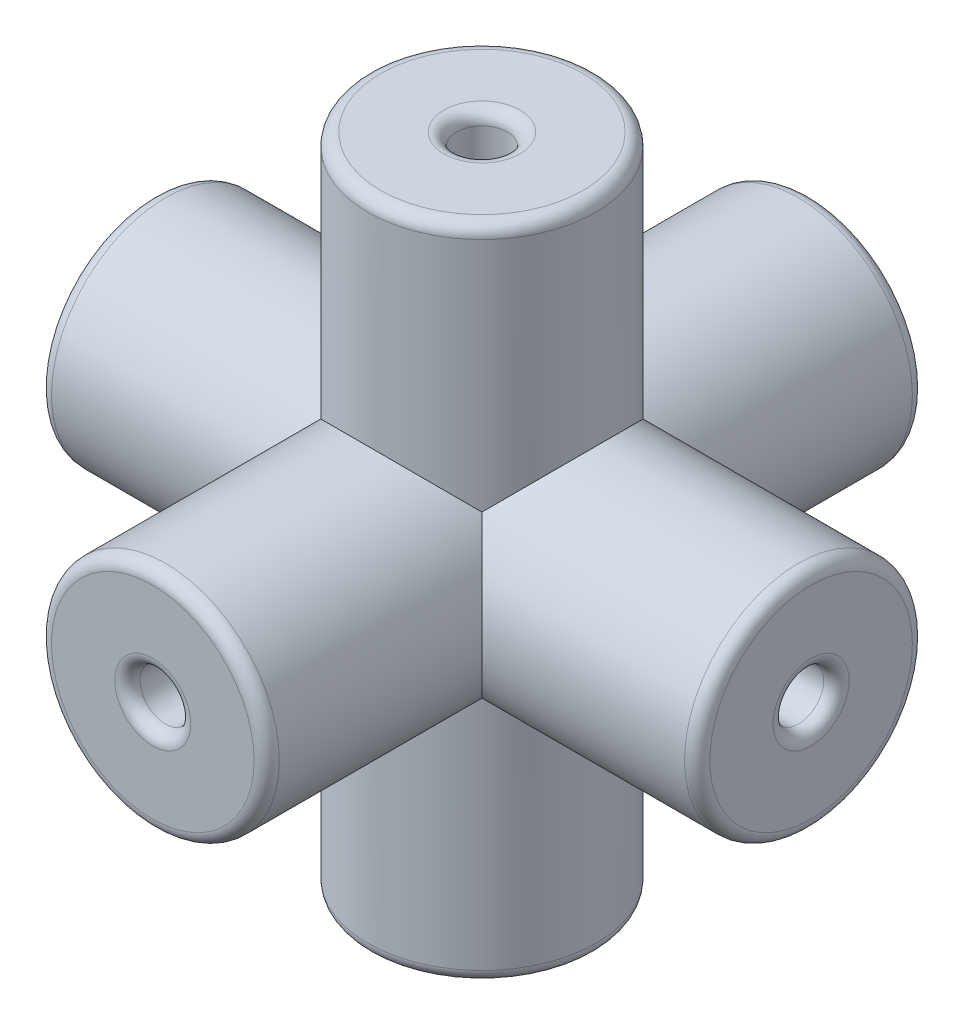
SolidWorks part; units mm, degrees
ref_plane "Front Plane" through (0, 0, 0) normal (0, 0, 1) x (1, 0, 0)
ref_plane "Top Plane" through (0, 0, 0) normal (0, 1, 0) x (1, 0, 0)
ref_plane "Right Plane" through (0, 0, 0) normal (1, 0, 0) x (0, 0, -1)
sketch "Sketch2" plane through (0, 0, 0) normal (0, 0, 1) x (1, 0, 0)
  circle A0 centre (0, 0) radius 4.5
  dimension "D1" = 9
extrude "Boss-Extrude4" add sketch "Sketch2" along normal mid plane 26 contours A0
sketch "Sketch6" plane through (0, 0, 0) normal (0, 1, 0) x (1, 0, 0)
  circle A0 centre (0, 0) radius 4.5
extrude "Boss-Extrude5" add sketch "Sketch6" along normal mid plane 26
sketch "Sketch7" plane through (0, 0, 0) normal (1, 0, 0) x (0, 0, -1)
  circle A0 centre (0, 0) radius 4.5
extrude "Boss-Extrude6" add sketch "Sketch7" along normal mid plane 26
hole_wizard "Ø2.0mm Dowel Hole1" positions "Sketch9" profile "Sketch8" hole size "Ø2.0" standard "ANSI Metric" end condition through all
sketch "Sketch9" plane through (0, 13, 0) normal (0, 1, 0) x (1, 0, 0)
  point P0 (0, 0)
sketch "Sketch8" plane through (0, 13, 0) normal (1, 0, 0) x (0, 0, 1)
  line L0 (0, 0) -> (0, 26)
  line L1 (0, 26) -> (1, 26)
  line L2 (1, 26) -> (1, 0)
  line L5 (1, 0) -> (0, 0)
  line L11 (0, -6.35) -> (0, 107.95) construction
  dimension "Thru Hole Dia." = 2
  dimension "Thru Hole Depth" = 26
hole_wizard "Ø2.0mm Dowel Hole2" positions "Sketch11" profile "Sketch10" hole size "Ø2.0" standard "ANSI Metric" end condition through all
sketch "Sketch11" plane through (-13, 0, 0) normal (-1, 0, 0) x (0, 0, 1)
  point P0 (0, 0)
sketch "Sketch10" plane through (-13, 0, 0) normal (0, 1, 0) x (0, 0, 1)
  line L0 (0, 0) -> (0, 26)
  line L1 (0, 26) -> (1, 26)
  line L2 (1, 26) -> (1, 0)
  line L5 (1, 0) -> (0, 0)
  line L11 (0, -6.35) -> (0, 107.95) construction
  dimension "Thru Hole Dia." = 2
  dimension "Thru Hole Depth" = 26
hole_wizard "Ø2.0mm Dowel Hole3" positions "Sketch13" profile "Sketch12" hole size "Ø2.0" standard "ANSI Metric" end condition through all
sketch "Sketch13" plane through (0, 0, 13) normal (0, 0, 1) x (1, 0, 0)
  point P0 (0, 0)
sketch "Sketch12" plane through (0, 0, 13) normal (1, 0, 0) x (0, -1, 0)
  line L0 (0, 0) -> (0, 26)
  line L1 (0, 26) -> (1, 26)
  line L2 (1, 26) -> (1, 0)
  line L5 (1, 0) -> (0, 0)
  line L11 (0, -6.35) -> (0, 107.95) construction
  dimension "Thru Hole Dia." = 2
  dimension "Thru Hole Depth" = 26
fillet "Fillet1" radius 0.5 12 edges at (0, -13, 1) (0, -13, 4.5) (-13, 0, -4.5) (-13, 0, 1) (0, 13, 1) (0, 13, 4.5) (4.5, 0, -13) (1, 0, -13) (1, 0, 13) (4.5, 0, 13) (13, 0, 1) (13, 0, -4.5)
